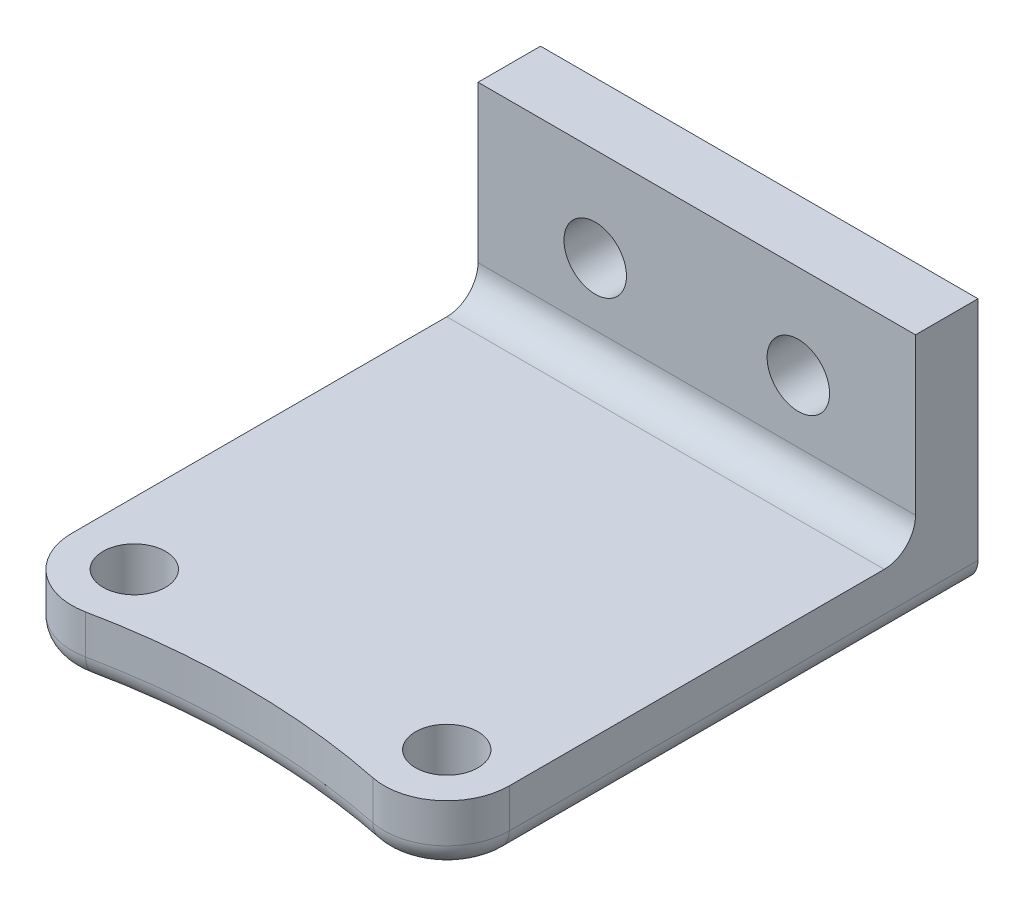
SolidWorks part; units mm, degrees
ref_plane "Front Plane" through (0, 0, 0) normal (0, 0, 1) x (1, 0, 0)
ref_plane "Top Plane" through (0, 0, 0) normal (0, 1, 0) x (1, 0, 0)
ref_plane "Right Plane" through (0, 0, 0) normal (1, 0, 0) x (0, 0, -1)
sketch "Sketch1" plane through (0, 0, 0) normal (0, 1, 0) x (1, 0, 0)
  line L0 (-4, 0) -> (-4, 30)
  line L1 (-4, 30) -> (24, 30)
  line L2 (24, 30) -> (24, 0)
  circle A0 centre (0, 0) radius 2
  circle A1 centre (20, 0) radius 2
  arc A3 (-4, 0) -> (0.8035, -3.9185) centre (0, 0) ccw
  arc A4 (19.1965, -3.9185) -> (24, 0) centre (20, 0) ccw
  arc A5 (19.1965, -3.9185) -> (0.8035, -3.9185) centre (10, -48.7663) ccw
extrude "Boss-Extrude1" add sketch "Sketch1" along normal blind 4
sketch "Sketch2" plane through (0, 4, 0) normal (0, 1, 0) x (1, 0, 0)
  line L0 (-4, 30) -> (-4, 26)
  line L1 (-4, 30) -> (-4, 0) construction
  line L2 (-4, 26) -> (24, 26)
  line L3 (24, 0) -> (24, 30) construction
  line L4 (24, 26) -> (24, 30)
  line L5 (24, 30) -> (-4, 30)
extrude "Boss-Extrude2" add sketch "Sketch2" along normal blind 12
sketch "Sketch3" plane through (0, 0, -26) normal (0, 0, 1) x (1, 0, 0)
  circle A2 centre (3.5, 10) radius 2
  circle A3 centre (16.5, 10) radius 2
  point P9 (10, 10)
extrude "Cut-Extrude1" cut sketch "Sketch3" against normal up to surface (4 mm away) up to face at (10, 8, -30)
fillet "Fillet1" radius 1.5 5 edges at (24, 0, -15) (22.5284, 0, 3.0995) (10, 0, 2.9853) (-2.5284, 0, 3.0995) (-4, 0, -15)
fillet "Fillet2" radius 2 1 edges at (10, 4, -26)
